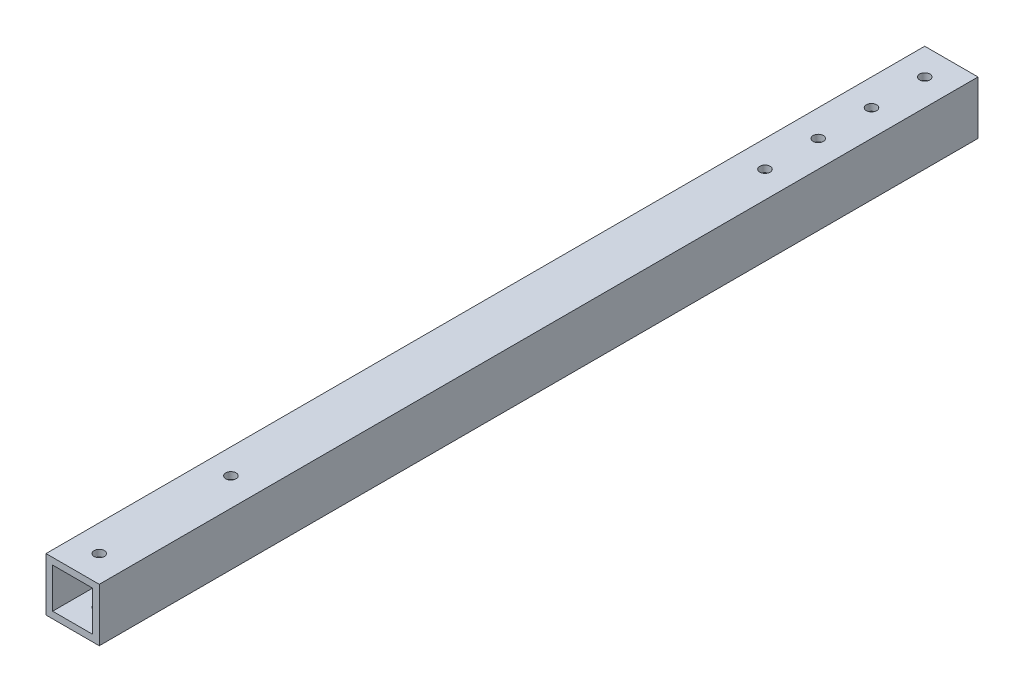
SolidWorks part; units mm, degrees
material "6061-T6 (SS)"
ref_plane "Front Plane" through (0, 0, 0) normal (0, 0, 1) x (1, 0, 0)
ref_plane "Top Plane" through (0, 0, 0) normal (0, 1, 0) x (1, 0, 0)
ref_plane "Right Plane" through (0, 0, 0) normal (1, 0, 0) x (0, 0, -1)
sketch "Sketch1" plane through (0, 0, 0) normal (0, 0, 1) x (1, 0, 0)
  line L0 (9.525, -9.525) -> (9.525, 9.525)
  line L1 (12.7, -12.7) -> (-12.7, -12.7)
  line L2 (12.7, -12.7) -> (12.7, 12.7)
  line L3 (12.7, 12.7) -> (-12.7, 12.7)
  line L4 (-12.7, -12.7) -> (-12.7, 12.7)
  line L5 (12.7, -12.7) -> (-12.7, 12.7) construction
  line L6 (12.7, 12.7) -> (-12.7, -12.7) construction
  line L7 (9.525, 9.525) -> (-9.525, 9.525)
  line L8 (-9.525, -9.525) -> (-9.525, 9.525)
  line L9 (9.525, -9.525) -> (-9.525, -9.525)
  point P0 (0, 0)
  dimension "D1" = 25.4
  dimension "D2" = 25.4
  dimension "D3" = 3.175
extrude "Boss-Extrude1" add sketch "Sketch1" along normal mid plane 482.6
sketch "Sketch2" plane through (0, 12.7, 0) normal (0, 1, 0) x (1, 0, 0)
  line L2 (12.7, 241.3) -> (-12.7, 241.3) construction
  line L3 (12.7, -241.3) -> (12.7, 241.3) construction
  point P0 (0, -228.6)
  point P1 (0, -228.6)
  point P3 (0, 88.9)
  dimension "D1" = 317.5
  dimension "D2" = 152.4
  dimension "D3" = 12.7
hole_wizard "#10 (0.1935) Diameter Hole1" positions "Sketch4" profile "Sketch3" hole size "#10" standard "ANSI Inch"
sketch "Sketch4" plane through (0, 12.7, 0) normal (0, 1, 0) x (1, 0, 0)
  point P0 (0, -228.6)
  point P3 (0, 88.9)
  point P12 (0, 114.3)
  point P13 (0, 139.7)
  point P18 (0, 165.1)
  point P19 (0, 190.5)
  point P20 (0, 215.9)
  dimension "D1" = 6
sketch "Sketch3" plane through (0, 12.7, 228.6) normal (1, 0, 0) x (0, 0, 1)
  line L0 (0, 0) -> (0, 52.2766)
  line L1 (0, 52.2766) -> (2.4574, 50.8)
  line L2 (2.4574, 50.8) -> (2.4574, 0)
  line L5 (2.4574, 0) -> (0, 0)
  line L10 (0, 52.2766) -> (-2.4575, 50.8) construction
  line L11 (0, -6.35) -> (0, 107.95) construction
  dimension "Hole Dia." = 4.9149
  dimension "Hole Depth" = 50.8
  dimension "Drill Angle" = 118
sketch "Sketch5" plane through (0, 12.7, 0) normal (0, 1, 0) x (1, 0, 0)
  circle A0 centre (-0.7064, -165.1039) radius 2.4642
  circle A1 centre (0, -228.6) radius 2.4574 construction
  dimension "D1" = 63.5
extrude "Cut-Extrude1" cut sketch "Sketch5" against normal through all
sketch "Sketch6" plane through (0, 12.7, 0) normal (0, 1, 0) x (1, 0, 0)
  line L0 (12.7, -241.3) -> (12.7, 241.3) construction
  line L1 (-12.7, 241.3) -> (12.7, 241.3)
  line L2 (-12.7, 241.3) -> (-12.7, 177.8)
  line L3 (-12.7, 177.8) -> (12.7, 177.8)
  line L4 (12.7, 241.3) -> (12.7, 177.8)
  dimension "D1" = 63.5
extrude "Cut-Extrude2" cut sketch "Sketch6" against normal through all
